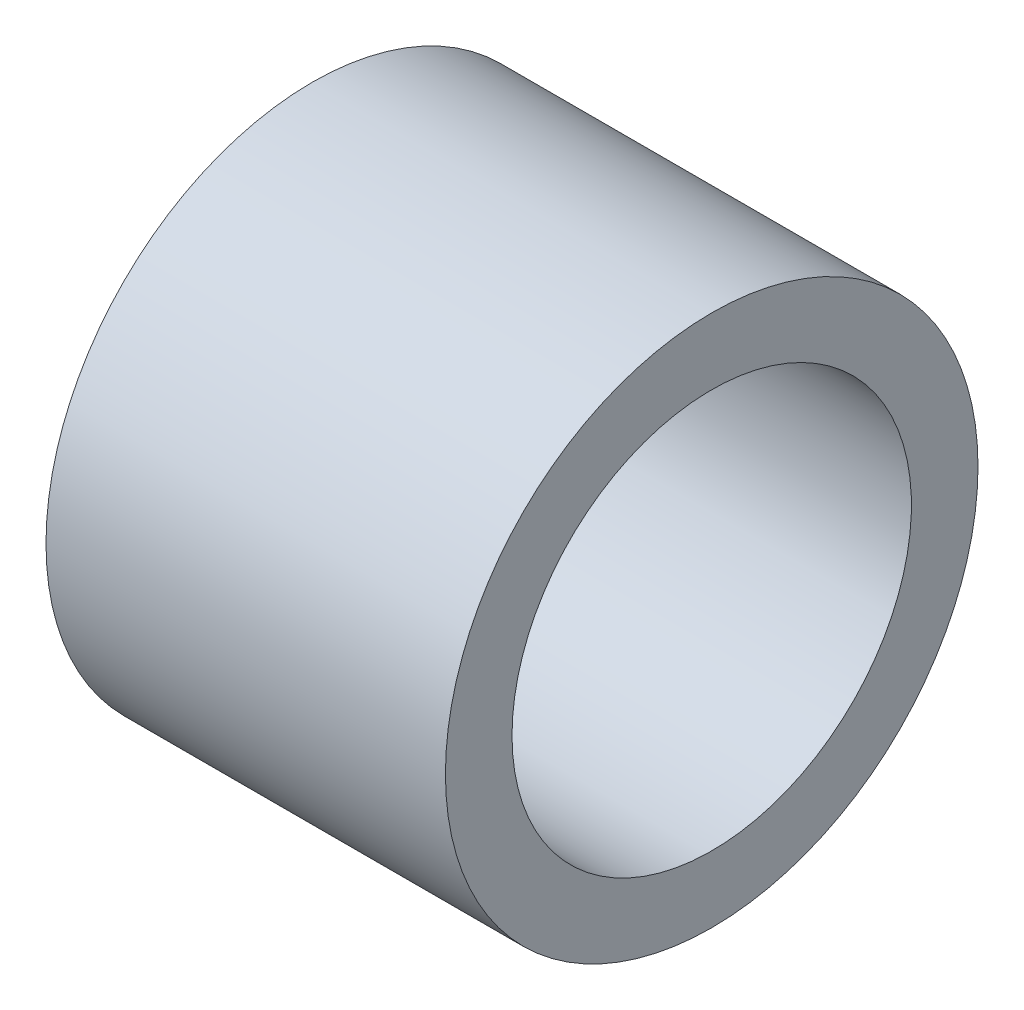
SolidWorks part; units mm, degrees
ref_plane "Front Plane" through (0, 0, 0) normal (0, 0, 1) x (1, 0, 0)
ref_plane "Top Plane" through (0, 0, 0) normal (0, 1, 0) x (1, 0, 0)
ref_plane "Right Plane" through (0, 0, 0) normal (1, 0, 0) x (0, 0, -1)
sketch "Sketch1" plane through (0, 0, 0) normal (1, 0, 0) x (0, 0, -1)
  circle A0 centre (0, 0) radius 12.7
  circle A1 centre (0, 0) radius 9.525
  dimension "D1" = 19.05
  dimension "D2" = 25.4
extrude "Boss-Extrude1" add sketch "Sketch1" along normal mid plane 19.05
